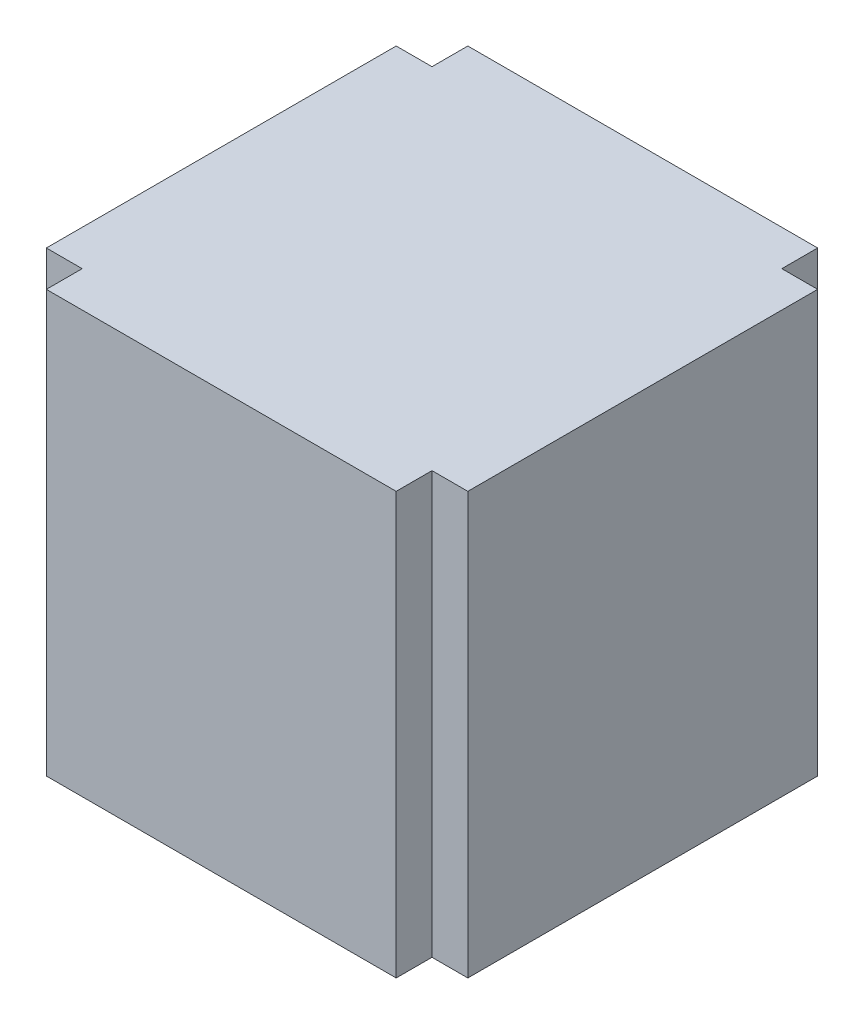
SolidWorks part; units mm, degrees
material "ABS"
ref_plane "Front Plane" through (0, 0, 0) normal (0, 0, 1) x (1, 0, 0)
ref_plane "Top Plane" through (0, 0, 0) normal (0, 1, 0) x (1, 0, 0)
ref_plane "Right Plane" through (0, 0, 0) normal (1, 0, 0) x (0, 0, -1)
sketch "Sketch1" plane through (0, 0, 0) normal (0, 1, 0) x (1, 0, 0)
  line L5 (-41.5, -41.5) -> (41.5, 41.5) construction
  line L6 (-41.5, 41.5) -> (41.5, -41.5) construction
  line L7 (41.5, 41.5) -> (50, 41.5)
  line L8 (41.5, -41.5) -> (50, -41.5)
  line L9 (50, 41.5) -> (50, -41.5)
  line L11 (-41.5, 41.5) -> (-41.5, 50)
  line L12 (41.5, 41.5) -> (41.5, 50)
  line L13 (-41.5, 50) -> (41.5, 50)
  line L15 (-41.5, 41.5) -> (-50, 41.5)
  line L16 (-41.5, -41.5) -> (-50, -41.5)
  line L17 (-50, 41.5) -> (-50, -41.5)
  line L19 (-41.5, -41.5) -> (-41.5, -50)
  line L20 (41.5, -41.5) -> (41.5, -50)
  line L21 (-41.5, -50) -> (41.5, -50)
  point P0 (0, 0)
  dimension "D1" = 83
  dimension "D2" = 83
  dimension "D3" = 83
  dimension "D4" = 83
  dimension "D5" = 8.5
extrude "Boss-Extrude1" add sketch "Sketch1" along normal mid plane 100
